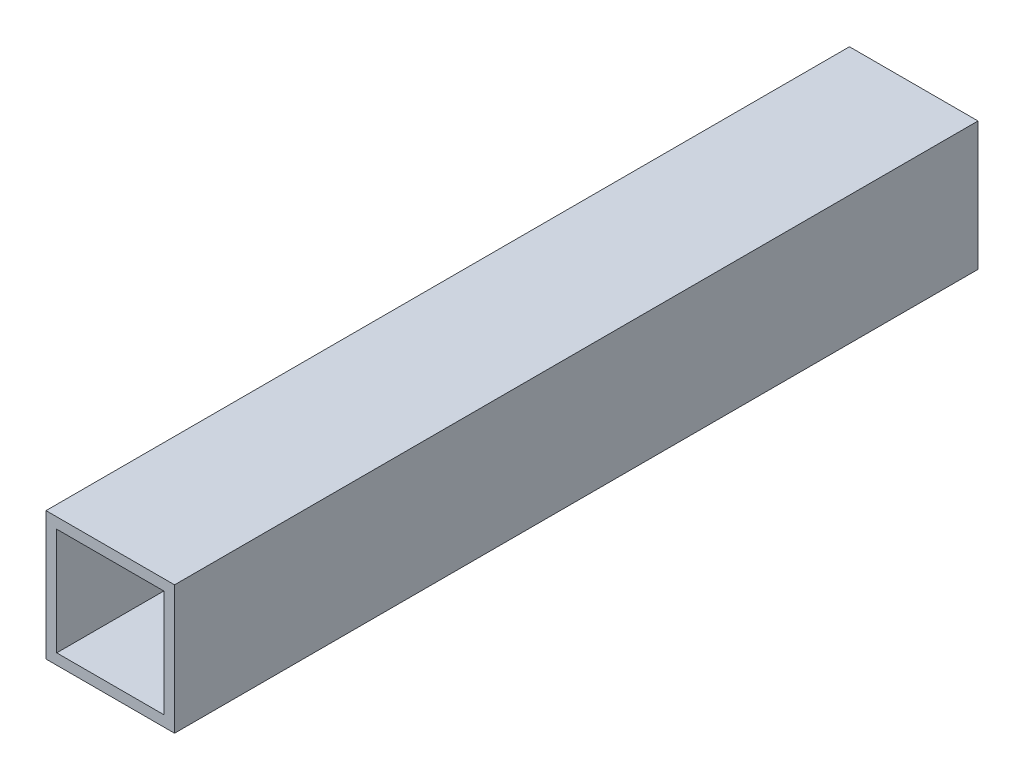
SolidWorks part; units mm, degrees
ref_plane "前视基准面" through (0, 0, 0) normal (0, 0, 1) x (1, 0, 0)
ref_plane "上视基准面" through (0, 0, 0) normal (0, 1, 0) x (1, 0, 0)
ref_plane "右视基准面" through (0, 0, 0) normal (1, 0, 0) x (0, 0, -1)
sketch "草图1" plane through (0, 0, 0) normal (0, 0, 1) x (1, 0, 0)
  line L0 (-12, 12) -> (12, 12)
  line L1 (-10, 10) -> (10, 10)
  line L2 (-10, 10) -> (-10, -10)
  line L3 (-10, -10) -> (10, -10)
  line L4 (10, 10) -> (10, -10)
  line L5 (-10, 10) -> (10, -10) construction
  line L6 (-10, -10) -> (10, 10) construction
  line L7 (12, 12) -> (12, -12)
  line L8 (-12, -12) -> (12, -12)
  line L9 (-12, 12) -> (-12, -12)
  point P0 (0, 0)
  dimension "D1" = 20
  dimension "D2" = 20
  dimension "D3" = 2
extrude "凸台-拉伸1" add sketch "草图1" along normal mid plane 150
